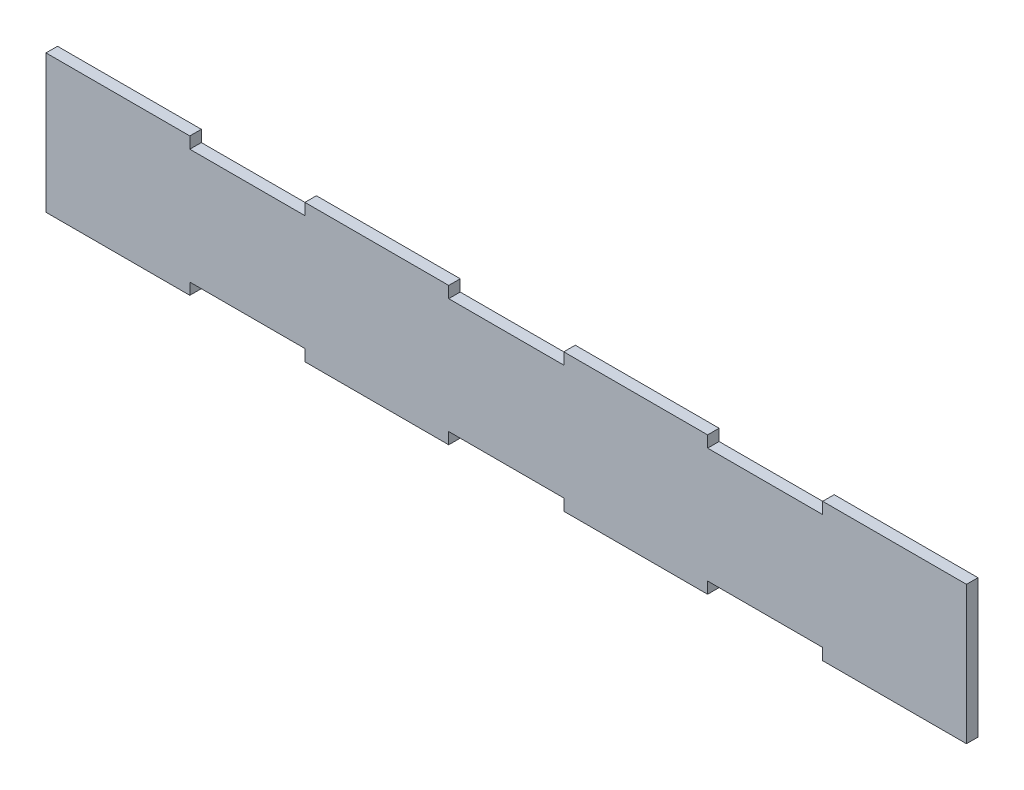
SolidWorks part; units mm, degrees
ref_plane "Спереди" through (0, 0, 0) normal (0, 0, 1) x (1, 0, 0)
ref_plane "Сверху" through (0, 0, 0) normal (0, 1, 0) x (1, 0, 0)
ref_plane "Справа" through (0, 0, 0) normal (1, 0, 0) x (0, 0, -1)
sketch "Эскиз1" plane through (0, 0, 0) normal (0, 0, 1) x (1, 0, 0)
  line L1 (0, 0) -> (160, 0)
  line L2 (0, 0) -> (0, 24)
  line L3 (0, 24) -> (160, 24)
  line L4 (160, 0) -> (160, 24)
  line L5 (25, 24) -> (45, 24)
  line L6 (25, 24) -> (25, 22)
  line L7 (25, 22) -> (45, 22)
  line L8 (45, 24) -> (45, 22)
  line L9 (70, 24) -> (90, 24)
  line L10 (70, 24) -> (70, 22)
  line L11 (70, 22) -> (90, 22)
  line L12 (90, 24) -> (90, 22)
  line L13 (115, 24) -> (135, 24)
  line L14 (115, 24) -> (115, 22)
  line L15 (115, 22) -> (135, 22)
  line L16 (135, 24) -> (135, 22)
  line L21 (25, 0) -> (45, 0)
  line L22 (25, 0) -> (25, 2)
  line L23 (25, 2) -> (45, 2)
  line L24 (45, 0) -> (45, 2)
  line L25 (70, 0) -> (90, 0)
  line L26 (70, 0) -> (70, 2)
  line L27 (70, 2) -> (90, 2)
  line L28 (90, 0) -> (90, 2)
  line L29 (115, 0) -> (135, 0)
  line L30 (115, 0) -> (115, 2)
  line L31 (115, 2) -> (135, 2)
  line L32 (135, 0) -> (135, 2)
  point P18 (0, 0)
  point P19 (0, 0)
  point P37 (0, 0)
  point P38 (139.7868, 27.7324)
  dimension "D1" = 24
  dimension "D2" = 160
  dimension "D3" = 2
  dimension "D4" = 2
  dimension "D5" = 2
  dimension "D6" = 2
  dimension "D7" = 20
  dimension "D8" = 20
  dimension "D9" = 20
  dimension "D10" = 2
  dimension "D11" = 2
  dimension "D12" = 20
  dimension "D13" = 20
  dimension "D14" = 20
  dimension "D15" = 25
  dimension "D16" = 25
  dimension "D17" = 25
  dimension "D18" = 25
  dimension "D19" = 25
  dimension "D20" = 25
extrude "Бобышка-Вытянуть1" add sketch "Эскиз1" along normal blind 2 contours L32 L1 L4 L3 L16 L15 L14 L12 L11 L10 L8 L7 L6 L2 L22 L23 L24 L26 L27 L28 L30 L31
